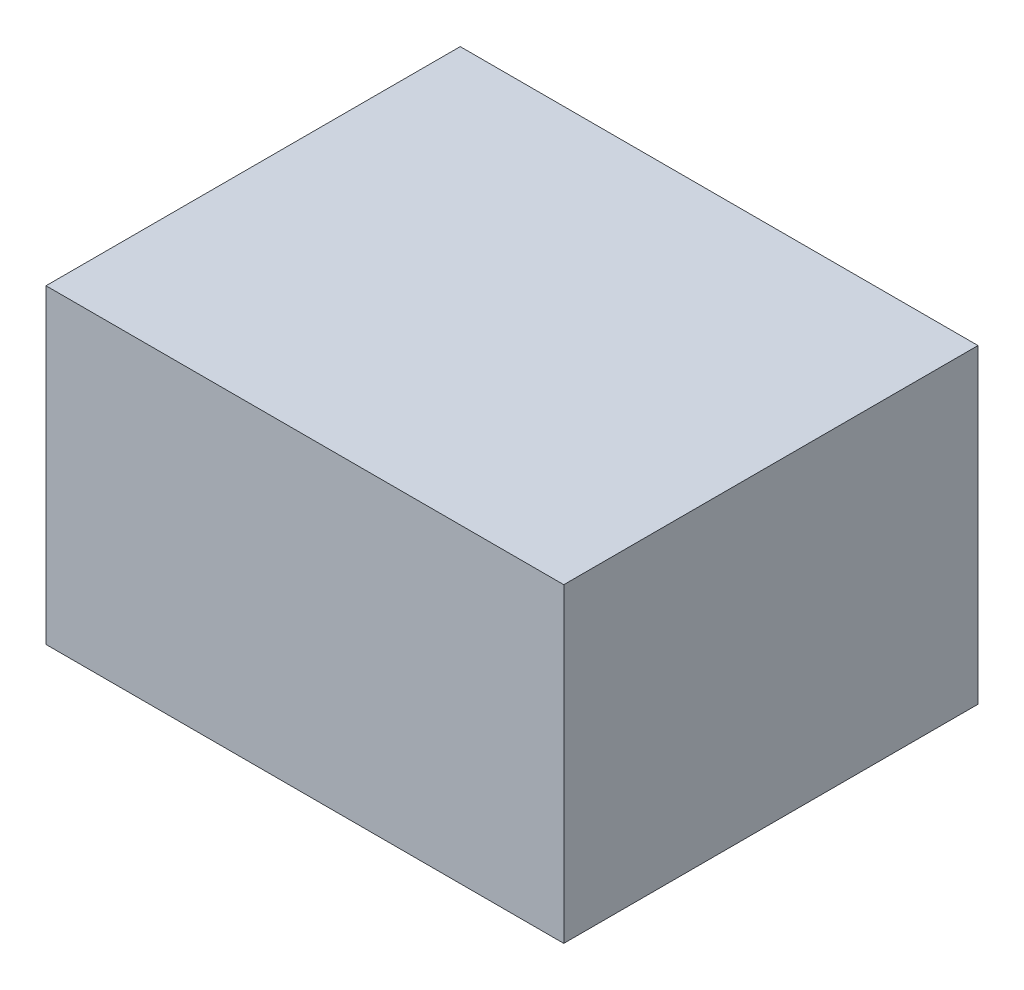
SolidWorks part; units mm, degrees
ref_plane "前视基准面" through (0, 0, 0) normal (0, 0, 1) x (1, 0, 0)
ref_plane "上视基准面" through (0, 0, 0) normal (0, 1, 0) x (1, 0, 0)
ref_plane "右视基准面" through (0, 0, 0) normal (1, 0, 0) x (0, 0, -1)
other "Configuration Table"
sketch "草图1" plane through (0, 0, 0) normal (0, 0, 1) x (1, 0, 0)
  line L1 (-12.5, 7.5) -> (12.5, 7.5)
  line L2 (-12.5, 7.5) -> (-12.5, -7.5)
  line L3 (-12.5, -7.5) -> (12.5, -7.5)
  line L4 (12.5, 7.5) -> (12.5, -7.5)
  line L5 (-12.5, 7.5) -> (12.5, -7.5) construction
  line L6 (-12.5, -7.5) -> (12.5, 7.5) construction
  point P0 (0, 0)
  dimension "D1" = 15
  dimension "D2" = 25
extrude "凸台-拉伸1" add sketch "草图1" along normal blind 20
